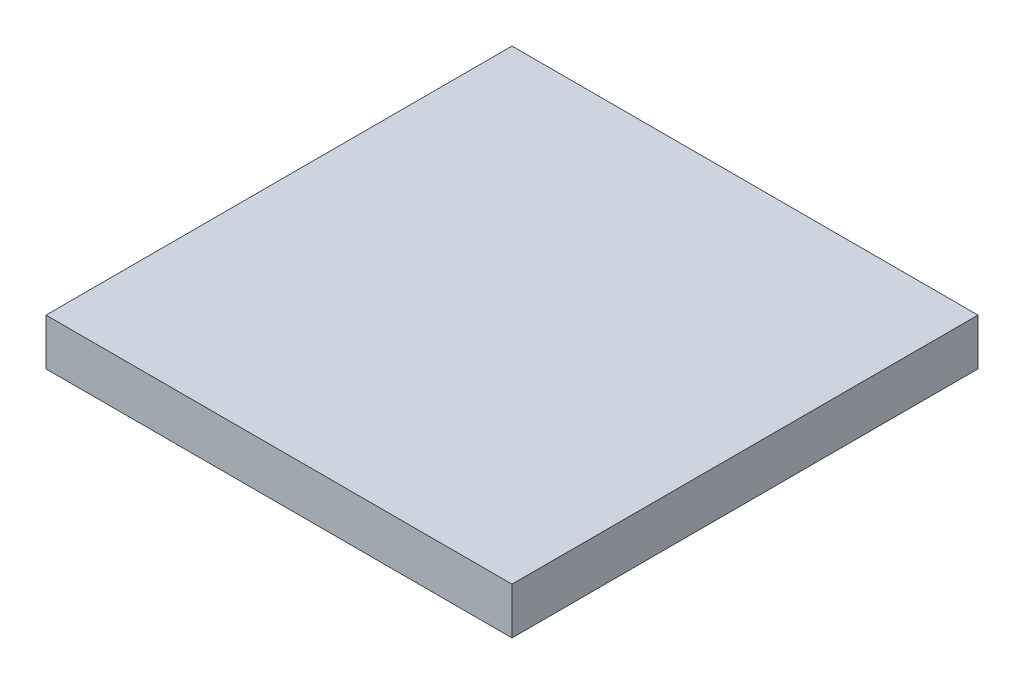
SolidWorks part; units mm, degrees
ref_plane "前视基准面" through (0, 0, 0) normal (0, 0, 1) x (1, 0, 0)
ref_plane "上视基准面" through (0, 0, 0) normal (0, 1, 0) x (1, 0, 0)
ref_plane "右视基准面" through (0, 0, 0) normal (1, 0, 0) x (0, 0, -1)
sketch "草图2" plane through (0, 0, 0) normal (0, 1, 0) x (1, 0, 0)
  line L1 (-50, -50) -> (50, -50)
  line L2 (-50, -50) -> (-50, 50)
  line L3 (-50, 50) -> (50, 50)
  line L4 (50, -50) -> (50, 50)
  line L5 (-50, -50) -> (50, 50) construction
  line L6 (-50, 50) -> (50, -50) construction
  point P0 (0, 0)
  dimension "D1" = 100
  dimension "D2" = 100
extrude "凸台-拉伸2" add sketch "草图2" along normal blind 10
